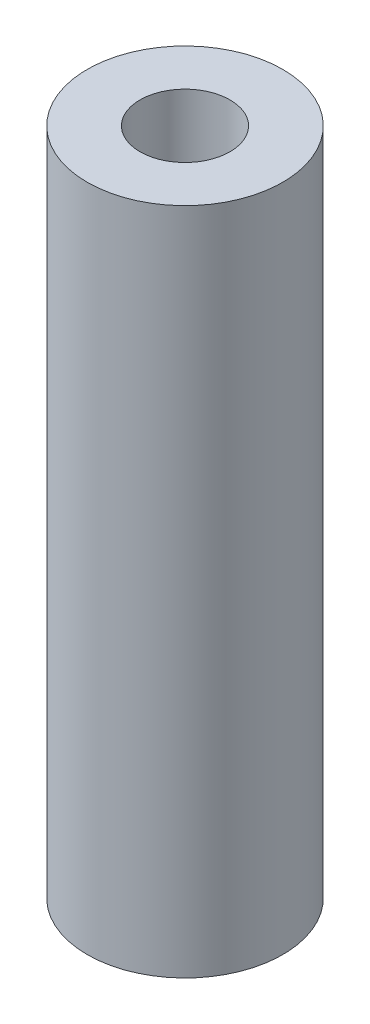
SolidWorks part; units mm, degrees
ref_plane "Front Plane" through (0, 0, 0) normal (0, 0, 1) x (1, 0, 0)
ref_plane "Top Plane" through (0, 0, 0) normal (0, 1, 0) x (1, 0, 0)
ref_plane "Right Plane" through (0, 0, 0) normal (1, 0, 0) x (0, 0, -1)
sketch "Sketch1" plane through (0, 0, 0) normal (0, 1, 0) x (1, 0, 0)
  circle A0 centre (0, 0) radius 5
  circle A1 centre (0, 0) radius 2.3
  dimension "D1" = 4.6
  dimension "D2" = 10
extrude "Boss-Extrude1" add sketch "Sketch1" along normal blind 34.2
